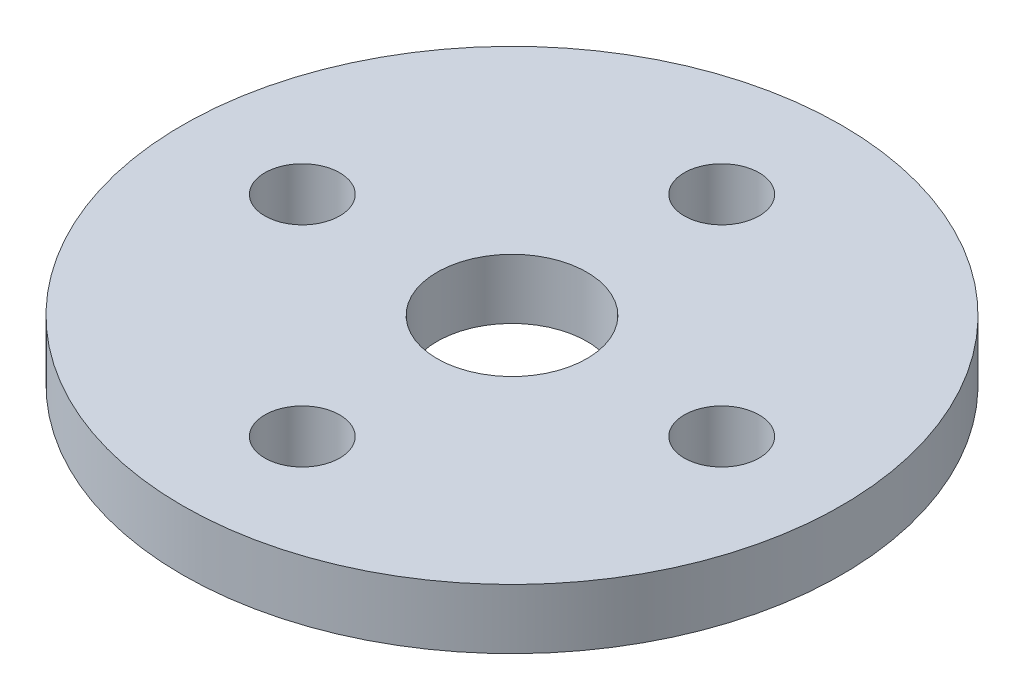
SolidWorks part; units mm, degrees
ref_plane "Front Plane" through (0, 0, 0) normal (0, 0, 1) x (1, 0, 0)
ref_plane "Top Plane" through (0, 0, 0) normal (0, 1, 0) x (1, 0, 0)
ref_plane "Right Plane" through (0, 0, 0) normal (1, 0, 0) x (0, 0, -1)
sketch "Sketch1" plane through (0, 0, 0) normal (0, 1, 0) x (1, 0, 0)
  circle A0 centre (0, 0) radius 11
  circle A1 centre (0, 0) radius 2.5
  circle A2 centre (0, 0) radius 7 construction
  circle A3 centre (0, 7) radius 1.25
  circle A4 centre (7, 0) radius 1.25
  circle A5 centre (0, -7) radius 1.25
  circle A6 centre (-7, 0) radius 1.25
  dimension "D1" = 5
  dimension "D2" = 14
  dimension "D3" = 22
  dimension "D4" = 2.5
extrude "Boss-Extrude1" add sketch "Sketch1" along normal blind 3
sketch "Sketch2" plane through (0, 3, 0) normal (0, 1, 0) x (1, 0, 0)
  circle A0 centre (0, 0) radius 11
extrude "Cut-Extrude1" cut sketch "Sketch2" against normal blind 1
